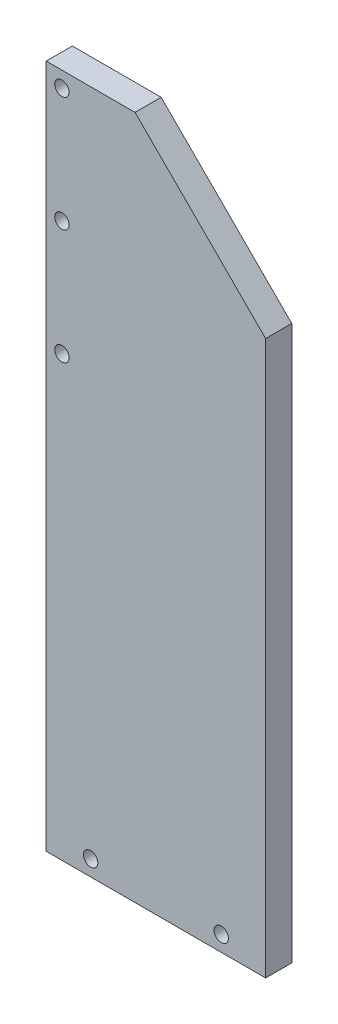
SolidWorks part; units mm, degrees
ref_plane "Front" through (0, 0, 0) normal (0, 0, 1) x (1, 0, 0)
ref_plane "Top" through (0, 0, 0) normal (0, 1, 0) x (1, 0, 0)
ref_plane "Right" through (0, 0, 0) normal (1, 0, 0) x (0, 0, -1)
sketch "Sketch1" plane through (0, 0, 0) normal (1, 0, 0) x (0, 0, -1)
  line L1 (0, 0) -> (-10, 0)
  line L2 (0, 0) -> (0, 262)
  line L3 (0, 262) -> (-10, 262)
  line L8 (-10, 262) -> (-10, 0)
  dimension "D2" = 262
  dimension "D3" = 10
extrude "Boss-Extrude1" add sketch "Sketch1" along normal mid plane 84
hole_wizard "CBORE for M5 Socket Head Cap Screw1" positions "Sketch2" profile "Sketch3" counterbore size "M5" standard "JIS" end condition through all
sketch "Sketch2" plane through (0, 0, 0) normal (0, 0, -1) x (-1, 0, 0)
  line L0 (-42, 262) -> (42, 262) construction
  line L1 (42, 0) -> (42, 262) construction
  point P0 (36, 256)
  point P1 (36, 212)
  point P3 (36, 168)
  dimension "D1" = 6
  dimension "D2" = 6
  dimension "D3" = 44
  dimension "D4" = 44
sketch "Sketch3" plane through (-36, 256, 0) normal (1, 0, 0) x (0, 1, 0)
  line L0 (0, 0) -> (0, 10)
  line L1 (0, 10) -> (2.75, 10)
  line L3 (2.75, 10) -> (2.75, 5)
  line L4 (2.75, 5) -> (5, 5)
  line L5 (5, 5) -> (5, 0)
  line L7 (5, 0) -> (0, 0)
  line L11 (0, -6.35) -> (0, 107.95) construction
  dimension "通し穴の直径" = 5.5
  dimension "通し穴の深さ" = 10
  dimension "座ぐり穴の直径" = 10
  dimension "座ぐり穴の深さ" = 5
hole_wizard "CBORE for M5 Socket Head Cap Screw2" positions "Sketch4" profile "Sketch5" counterbore size "M5" standard "JIS" end condition through all
sketch "Sketch4" plane through (0, 0, 0) normal (0, 0, -1) x (-1, 0, 0)
  line L0 (0, 50.1859) -> (0, -11.5042) construction
  line L2 (-42, 0) -> (42, 0) construction
  point P0 (-25, 6)
  point P1 (25, 6)
  dimension "D1" = 6
  dimension "D2" = 50
sketch "Sketch5" plane through (25, 6, 0) normal (1, 0, 0) x (0, 1, 0)
  line L0 (0, 0) -> (0, 10)
  line L1 (0, 10) -> (2.75, 10)
  line L3 (2.75, 10) -> (2.75, 5)
  line L4 (2.75, 5) -> (5, 5)
  line L5 (5, 5) -> (5, 0)
  line L7 (5, 0) -> (0, 0)
  line L11 (0, -6.35) -> (0, 107.95) construction
  dimension "通し穴の直径" = 5.5
  dimension "通し穴の深さ" = 10
  dimension "座ぐり穴の直径" = 10
  dimension "座ぐり穴の深さ" = 5
chamfer "Chamfer1" distance 50 angle 45 1 edges at (42, 262, 5)
